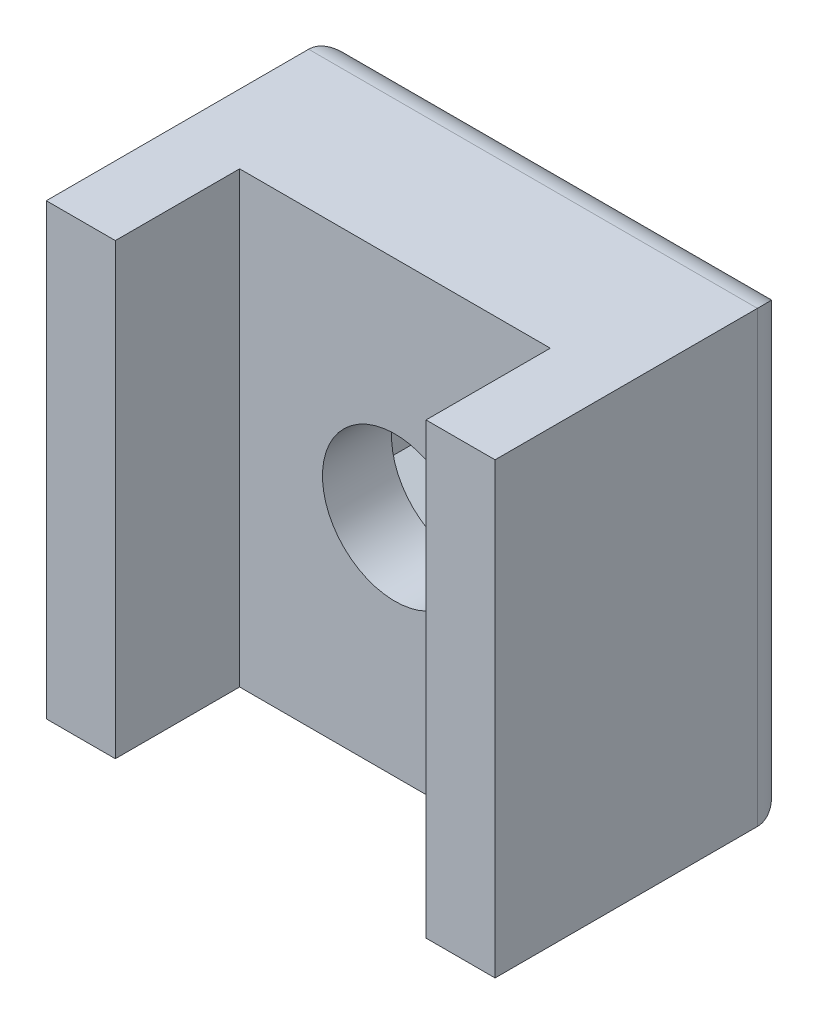
SolidWorks part; units mm, degrees
ref_plane "Plan de face" through (0, 0, 0) normal (0, 0, 1) x (1, 0, 0)
ref_plane "Plan de dessus" through (0, 0, 0) normal (0, 1, 0) x (1, 0, 0)
ref_plane "Plan de droite" through (0, 0, 0) normal (1, 0, 0) x (0, 0, -1)
sketch "Esquisse1" plane through (0, 0, 0) normal (0, 0, 1) x (1, 0, 0)
  line L1 (-6.5, -6.5) -> (6.5, -6.5)
  line L2 (-6.5, -6.5) -> (-6.5, 6.5)
  line L3 (-6.5, 6.5) -> (6.5, 6.5)
  line L4 (6.5, -6.5) -> (6.5, 6.5)
  line L5 (-6.5, -6.5) -> (6.5, 6.5) construction
  line L6 (-6.5, 6.5) -> (6.5, -6.5) construction
  point P0 (0, 0)
  dimension "D1" = 13
  dimension "D2" = 13
extrude "Boss.-Extru.1" add sketch "Esquisse1" along normal blind 5.6
sketch "Esquisse2" plane through (0, 0, 5.6) normal (0, 0, 1) x (1, 0, 0)
  line L0 (6.5, 6.5) -> (-6.5, 6.5) construction
  line L1 (-4.5, -6.5) -> (4.5, -6.5)
  line L2 (-4.5, -6.5) -> (-4.5, 6.5)
  line L3 (-4.5, 6.5) -> (4.5, 6.5)
  line L4 (4.5, -6.5) -> (4.5, 6.5)
  line L5 (-4.5, -6.5) -> (4.5, 6.5) construction
  line L6 (-4.5, 6.5) -> (4.5, -6.5) construction
  line L7 (-6.5, 6.5) -> (-6.5, -6.5) construction
  line L8 (6.5, -6.5) -> (6.5, 6.5) construction
  point P0 (0, 0)
  dimension "D1" = 2
  dimension "D2" = 2
  dimension "D3" = 9
extrude "Enlèv. mat.-Extru.1" cut sketch "Esquisse2" against normal blind 3.6
sketch "Esquisse3" plane through (0, 0, 2) normal (0, 0, 1) x (1, 0, 0)
  circle A0 centre (0, 0) radius 2.1
  dimension "D1" = 4.2
extrude "Enlèv. mat.-Extru.2" cut sketch "Esquisse3" against normal through all
sketch "Esquisse4" plane through (0, 0, 0) normal (0, 0, -1) x (-1, 0, 0)
  line L0 (-6.5, -6.5) -> (-6.5, 6.5) construction
  line L1 (-3.75, -2.1651) -> (0, -4.3301)
  line L2 (0, -4.3301) -> (3.75, -2.1651)
  line L3 (3.75, -2.1651) -> (3.75, 2.1651)
  line L4 (3.75, 2.1651) -> (0, 4.3301)
  line L5 (0, 4.3301) -> (-3.75, 2.1651)
  line L6 (-3.75, 2.1651) -> (-3.75, -2.1651)
  line L10 (6.5, -6.5) -> (-6.5, -6.5)
  line L11 (6.5, -6.5) -> (6.5, 6.5)
  line L12 (6.5, 6.5) -> (-6.5, 6.5)
  line L13 (-6.5, -6.5) -> (-6.5, 6.5)
  line L14 (6.5, -6.5) -> (-6.5, 6.5) construction
  line L15 (6.5, 6.5) -> (-6.5, -6.5) construction
  circle A0 centre (0, 0) radius 3.75 construction
  dimension "D1" = 7.5
extrude "Boss.-Extru.2" add sketch "Esquisse4" along normal blind 3
fillet "Congé1" radius 1 4 edges at (-6.5, 0, -3) (6.5, 0, -3) (0, -6.5, -3) (0, 6.5, -3)
